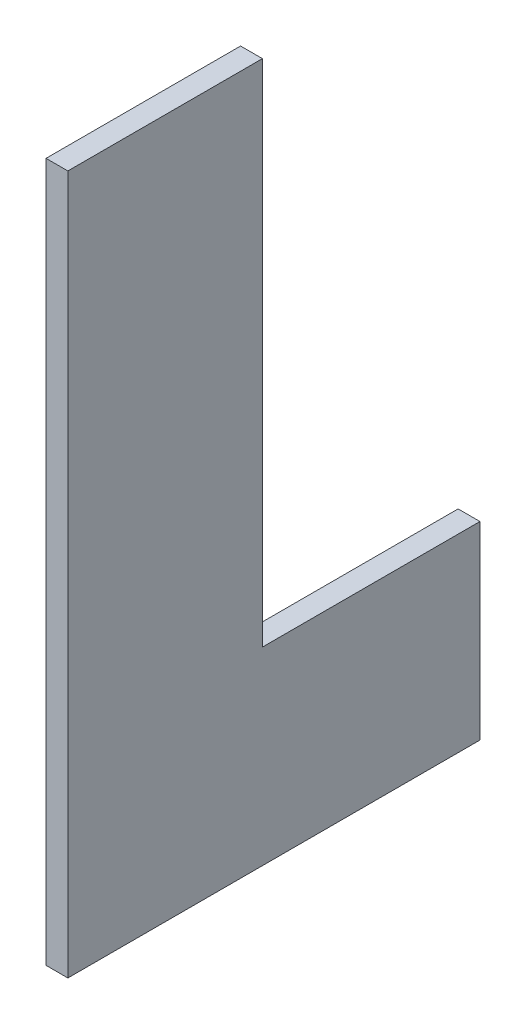
SolidWorks part; units mm, degrees
material "Plywood"
ref_plane "Front Plane" through (0, 0, 0) normal (0, 0, 1) x (1, 0, 0)
ref_plane "Top Plane" through (0, 0, 0) normal (0, 1, 0) x (1, 0, 0)
ref_plane "Right Plane" through (0, 0, 0) normal (1, 0, 0) x (0, 0, -1)
sketch "Sketch1" plane through (0, 0, 0) normal (1, 0, 0) x (0, 0, -1)
  line L0 (102.7058, -525.3522) -> (292.4438, -525.3522)
  line L1 (-66.9662, 84.2478) -> (102.7058, 84.2478)
  line L2 (-66.9662, 84.2478) -> (-66.9662, -525.3522)
  line L3 (-66.9662, -525.3522) -> (102.7058, -525.3522)
  line L5 (-66.9662, 84.2478) -> (102.7058, -525.3522) construction
  line L6 (-66.9662, -525.3522) -> (102.7058, 84.2478) construction
  line L7 (292.4438, -525.3522) -> (292.4438, -360.2522)
  line L8 (292.4438, -360.2522) -> (102.7058, -360.2522)
  line L9 (102.7058, -360.2522) -> (102.7058, 84.2478)
  point P0 (17.8698, -220.5522)
  dimension "D1" = 169.672
  dimension "D2" = 609.6
  dimension "D3" = 165.1
  dimension "D4" = 189.738
extrude "Boss-Extrude1" add sketch "Sketch1" along normal blind 19.05
